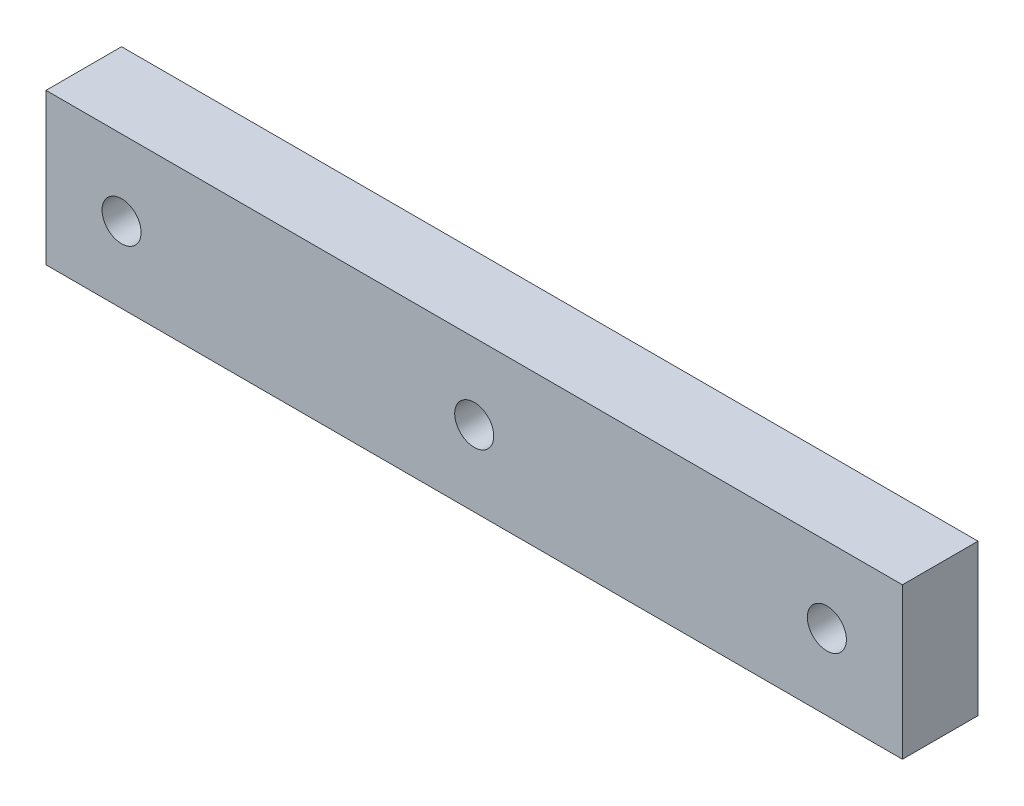
SolidWorks part; units mm, degrees
ref_plane "Płaszczyzna przednia" through (0, 0, 0) normal (0, 0, 1) x (1, 0, 0)
ref_plane "Płaszczyzna górna" through (0, 0, 0) normal (0, 1, 0) x (1, 0, 0)
ref_plane "Płaszczyzna prawa" through (0, 0, 0) normal (1, 0, 0) x (0, 0, -1)
sketch "Szkic1" plane through (0, 0, 0) normal (0, 0, 1) x (1, 0, 0)
  line L0 (115.2015, 17.704) -> (47.2015, 17.704)
  line L1 (115.2015, 17.704) -> (115.2015, 5.704)
  line L2 (47.2015, 17.704) -> (47.2015, 5.704)
  line L3 (115.2015, 5.704) -> (47.2015, 5.704)
  dimension "D1" = 12
extrude "Dodanie-wyciągnięcie1" add sketch "Szkic1" along normal blind 6
sketch "Szkic2" plane through (0, 0, 6) normal (0, 0, 1) x (1, 0, 0)
  line L0 (47.2015, 17.704) -> (47.2015, 5.704) construction
  line L1 (115.2015, 5.704) -> (115.2015, 17.704) construction
  line L2 (115.2015, 17.704) -> (47.2015, 17.704) construction
  line L3 (135.2015, 17.704) -> (27.2015, 17.704) construction
  circle A0 centre (109.2015, 11.704) radius 1.55
  circle A1 centre (53.2015, 11.704) radius 1.55
  circle A2 centre (81.2015, 11.704) radius 1.55
  dimension "D1" = 3.1
  dimension "D2" = 3.1
  dimension "D3" = 3.1
  dimension "D4" = 6
  dimension "D5" = 6
  dimension "D6" = 34
  dimension "D7" = 6
  dimension "D8" = 6
  dimension "D9" = 6
extrude "Wytnij-wyciągnięcie1" cut sketch "Szkic2" against normal blind 6
equation "\"tolerancja_wpusy\"=0.2"
equation "\"dlugosc_wpustu_duzy\"=20"
equation "\"srednica_otworu_M3\"=3.1"
equation "\"szerokosc_nogi_T\"=3.1"
equation "\"dlugosc_T_30\"=11"
equation "\"grubosc_na_nakretke_kwadrat\"=2"
equation "\"szerokosc_na_nakretke_kwadrat\"=5.85"
equation "\"wyokosc_nadstawki_T\"=0.5"
equation "\"dlugosc_T_20_6\"=14"
equation "\"D1@Szkic2\"=\"srednica_otworu_M3\""
equation "\"D2@Szkic2\"=\"srednica_otworu_M3\""
equation "\"D3@Szkic2\"=\"srednica_otworu_M3\""
